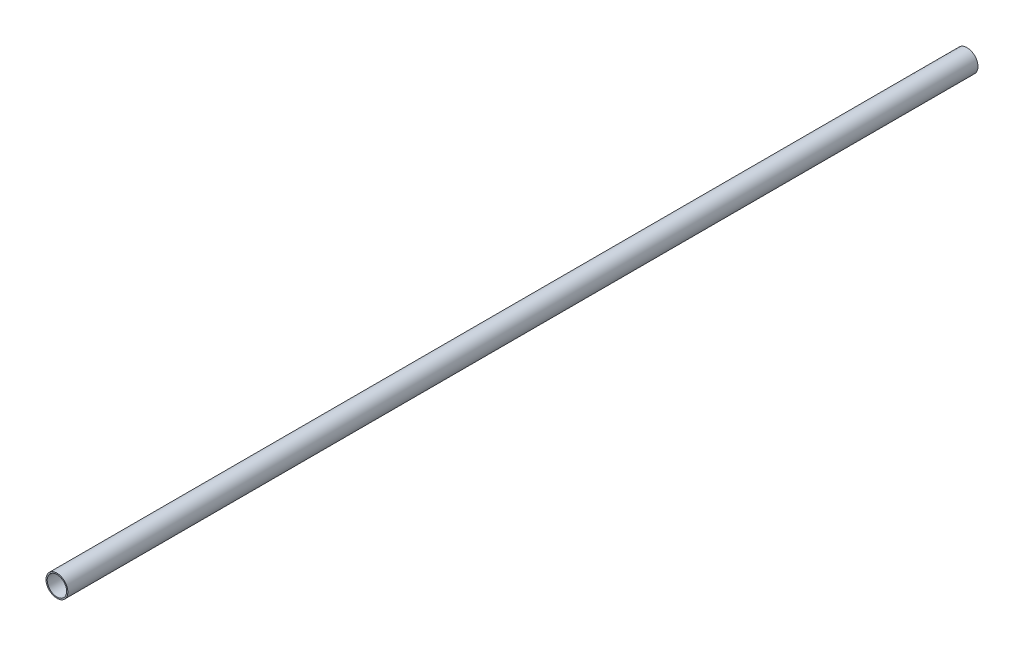
SolidWorks part; units mm, degrees
material "AISI 4130 Steel, annealed at 865C"
ref_plane "Front Plane" through (0, 0, 0) normal (0, 0, 1) x (1, 0, 0)
ref_plane "Top Plane" through (0, 0, 0) normal (0, 1, 0) x (1, 0, 0)
ref_plane "Right Plane" through (0, 0, 0) normal (1, 0, 0) x (0, 0, -1)
sketch "Sketch1" plane through (0, 0, 0) normal (0, 0, 1) x (1, 0, 0)
  circle A0 centre (0, 0) radius 7.9375
  circle A1 centre (0, 0) radius 7.0485
  dimension "D1" = 15.875
  dimension "D2" = 0.889
extrude "Boss-Extrude1" add sketch "Sketch1" along normal mid plane 660.4
